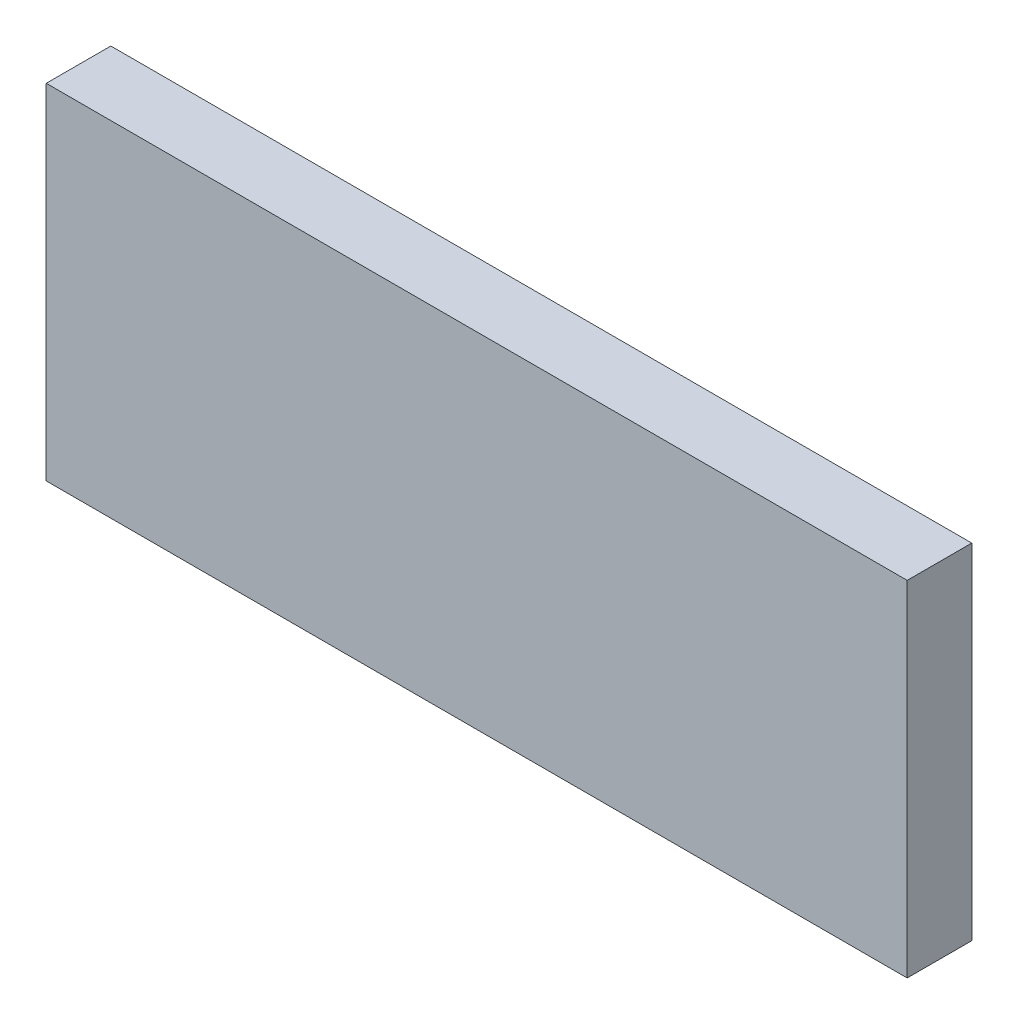
SolidWorks part; units mm, degrees
material "1.0038 (S235JRG2)"
ref_plane "Ebene vorne" through (0, 0, 0) normal (0, 0, 1) x (1, 0, 0)
ref_plane "Ebene oben" through (0, 0, 0) normal (0, 1, 0) x (1, 0, 0)
ref_plane "Ebene rechts" through (0, 0, 0) normal (1, 0, 0) x (0, 0, -1)
sketch "Skizze1" plane through (0, 0, 0) normal (0, 0, 1) x (1, 0, 0)
  line L1 (-100, -40) -> (100, -40)
  line L2 (-100, -40) -> (-100, 40)
  line L3 (-100, 40) -> (100, 40)
  line L4 (100, -40) -> (100, 40)
  dimension "D1" = 200
  dimension "D2" = 80
  dimension "D3" = 100
  dimension "D4" = 40
extrude "Aufsatz-Linear austragen1" add sketch "Skizze1" along normal blind 15
